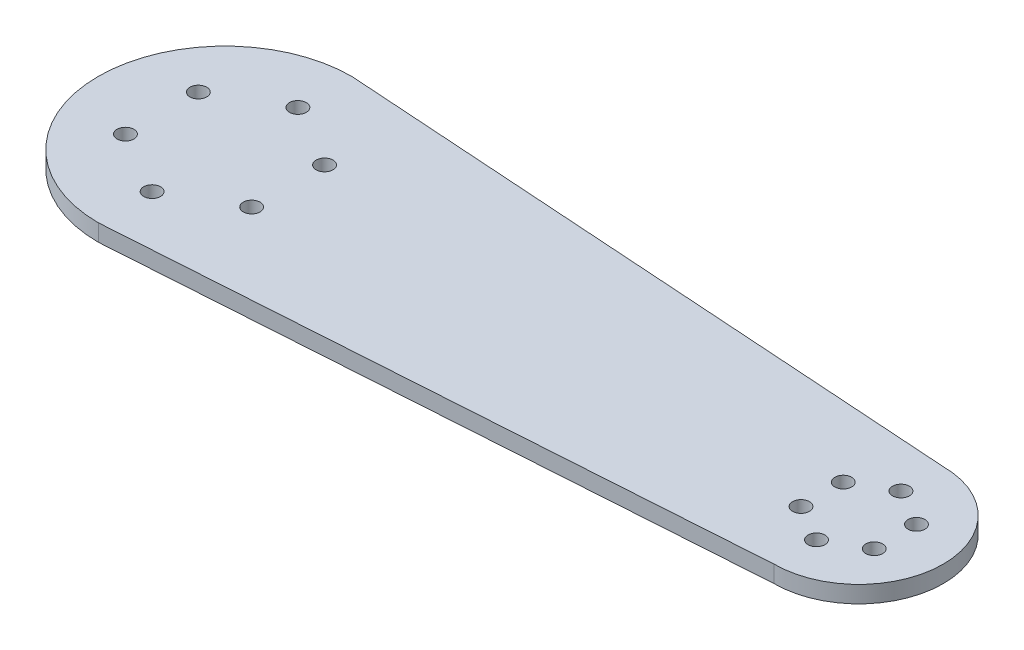
SolidWorks part; units mm, degrees
ref_plane "前视基准面" through (0, 0, 0) normal (0, 0, 1) x (1, 0, 0)
ref_plane "上视基准面" through (0, 0, 0) normal (0, 1, 0) x (1, 0, 0)
ref_plane "右视基准面" through (0, 0, 0) normal (1, 0, 0) x (0, 0, -1)
other "Configuration Table"
sketch "草图1" plane through (0, 0, 0) normal (0, 1, 0) x (1, 0, 0)
  line L0 (0, 0) -> (150, 0)
  line L1 (0, 30) -> (150, 20)
  line L2 (0, -30) -> (150, -20)
  circle A0 centre (0, 0) radius 30
  circle A1 centre (0, 0) radius 17.25
  circle A2 centre (0, 17.25) radius 2
  circle A3 centre (14.9389, 8.625) radius 2
  circle A4 centre (14.9389, -8.625) radius 2
  circle A5 centre (0, -17.25) radius 2
  circle A6 centre (-14.9389, -8.625) radius 2
  circle A7 centre (-14.9389, 8.625) radius 2
  circle A8 centre (150, 0) radius 20
  circle A9 centre (150, 0) radius 10
  circle A10 centre (150, 10) radius 2
  circle A11 centre (158.6603, 5) radius 2
  circle A12 centre (158.6603, -5) radius 2
  circle A13 centre (150, -10) radius 2
  circle A14 centre (141.3397, -5) radius 2
  circle A15 centre (141.3397, 5) radius 2
  dimension "D1" = 60
  dimension "D2" = 34.5
  dimension "D3" = 4
  dimension "D6" = 40
  dimension "D7" = 20
  dimension "D8" = 4
  dimension "D5" = 150
  dimension "D4" = 6
  dimension "D9" = 6
extrude "凸台-拉伸2" add sketch "草图1" along normal blind 4
